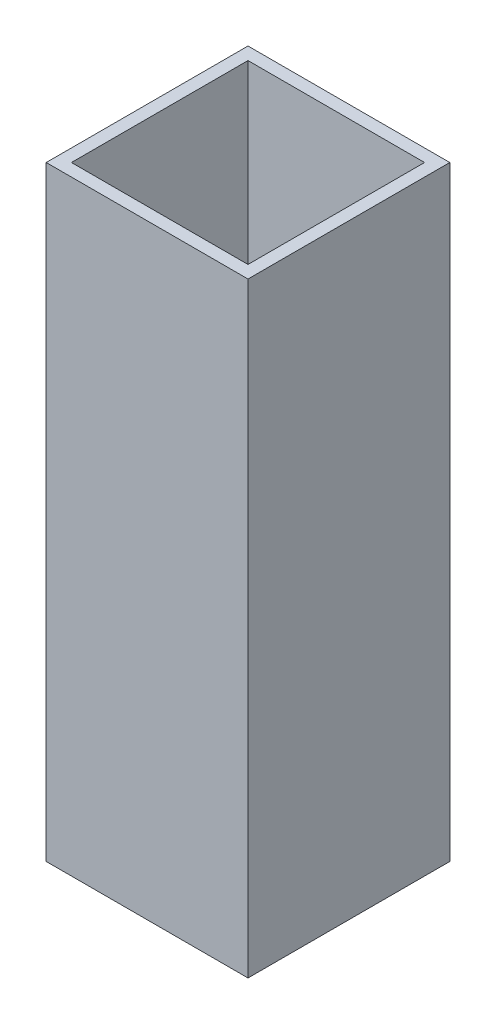
SolidWorks part; units mm, degrees
ref_plane "Front Plane" through (0, 0, 0) normal (0, 0, 1) x (1, 0, 0)
ref_plane "Top Plane" through (0, 0, 0) normal (0, 1, 0) x (1, 0, 0)
ref_plane "Right Plane" through (0, 0, 0) normal (1, 0, 0) x (0, 0, -1)
sketch "Sketch1" plane through (0, 0, 0) normal (0, 1, 0) x (1, 0, 0)
  line L1 (12.7, -12.7) -> (-12.7, -12.7)
  line L2 (12.7, -12.7) -> (12.7, 12.7)
  line L3 (12.7, 12.7) -> (-12.7, 12.7)
  line L4 (-12.7, -12.7) -> (-12.7, 12.7)
  line L5 (12.7, -12.7) -> (-12.7, 12.7) construction
  line L6 (12.7, 12.7) -> (-12.7, -12.7) construction
  line L7 (11.1125, -11.1125) -> (-11.1125, -11.1125)
  line L9 (11.1125, -11.1125) -> (11.1125, 11.1125)
  line L10 (11.1125, 11.1125) -> (-11.1125, 11.1125)
  line L11 (9.9974, -9.9974) -> (-9.9974, 9.9974) construction
  line L12 (9.9974, 9.9974) -> (-9.9974, -9.9974) construction
  line L13 (-11.1125, -11.1125) -> (-11.1125, 11.1125)
  line L14 (11.1125, -11.1125) -> (-11.1125, 11.1125) construction
  line L15 (11.1125, 11.1125) -> (-11.1125, -11.1125) construction
  point P0 (0, 0)
  point P6 (0, 0)
  point P11 (0, 0)
  dimension "D1" = 25.4
  dimension "D2" = 25.4
extrude "Boss-Extrude1" add sketch "Sketch1" along normal blind 76.2
